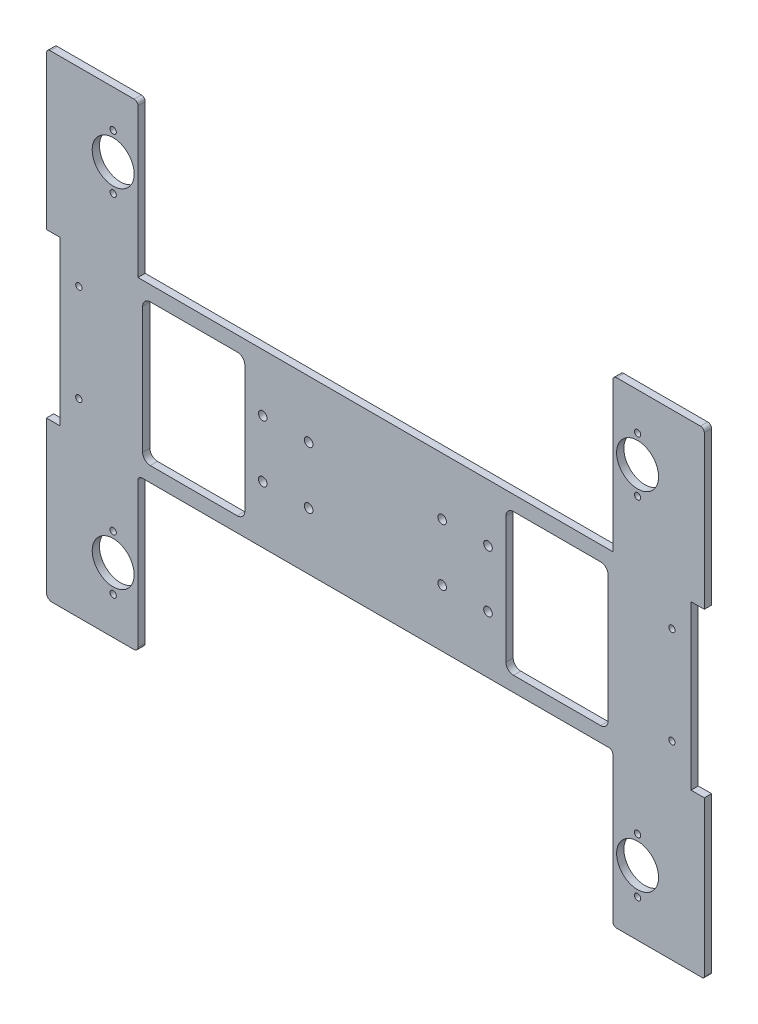
SolidWorks part; units mm, degrees
ref_plane "Front Plane" through (0, 0, 0) normal (0, 0, 1) x (1, 0, 0)
ref_plane "Top Plane" through (0, 0, 0) normal (0, 1, 0) x (1, 0, 0)
ref_plane "Right Plane" through (0, 0, 0) normal (1, 0, 0) x (0, 0, -1)
ref_plane "Plane1" through (0, 150, 0) normal (0, 1, 0) x (1, 0, 0)
ref_plane "Plane2" through (0, -150, 0) normal (0, 1, 0) x (1, 0, 0)
ref_plane "Plane3" through (150, 0, 0) normal (1, 0, 0) x (0, 0, -1)
ref_plane "Plane4" through (-150, 0, 0) normal (1, 0, 0) x (0, 0, -1)
sketch "Sketch2" plane through (0, 0, 0) normal (0, 0, 1) x (1, 0, 0)
  line L0 (0, -10.2) -> (0, 50.0764) construction
  line L5 (-59.06, 39.945) -> (-59.06, 10.055) construction
  line L23 (-170.5, 150) -> (-126.5, 150)
  line L24 (139.6652, 116) -> (168.3348, 116) construction
  line L30 (-172.5, 148) -> (-172.5, 67.8042)
  line L31 (-169.5, -100) -> (-126.5, -100)
  line L39 (172.5, 148) -> (172.5, 67.8042)
  line L40 (-152.1866, -81.0661) -> (-123.5266, -81.0661) construction
  line L42 (-124.5, 148) -> (-124.5, 70)
  line L43 (-124.5, 70) -> (124.5, 70)
  line L44 (124.5, 148) -> (124.5, 70)
  line L45 (126.5, 150) -> (170.5, 150)
  line L47 (-72.4574, 62.1714) -> (-118.0552, 62.1714)
  line L48 (72.4574, 62.1714) -> (118.0552, 62.1714)
  line L49 (68.4574, 58.1714) -> (68.4574, -8.1714)
  line L50 (72.4574, -12.1714) -> (118.0552, -12.1714)
  line L51 (122.0552, 58.1714) -> (122.0552, -8.1714)
  line L52 (68.4574, 62.1714) -> (122.0552, -12.1714) construction
  line L53 (68.4574, -12.1714) -> (122.0552, 62.1714) construction
  line L54 (-68.4574, 58.1714) -> (-68.4574, -8.1714)
  line L55 (-72.4574, -12.1714) -> (-118.0552, -12.1714)
  line L56 (-122.0552, 58.1714) -> (-122.0552, -8.1714)
  line L57 (177.1787, -66.0847) -> (177.1787, 11.9153) construction
  line L61 (165.5, 67.8042) -> (165.5, -17.8042)
  line L62 (165.5, -17.8042) -> (172.5, -17.8042)
  line L63 (172.5, 67.8042) -> (165.5, 67.8042)
  line L65 (172.5, -17.8042) -> (172.5, -99)
  line L66 (177.1787, 0) -> (1253.7576, 0) construction
  line L67 (-165.5, 67.8042) -> (-165.5, -17.8042)
  line L69 (-172.5, -17.8042) -> (-172.5, -97)
  line L70 (-155.5, 50.5) -> (-155.5, -0.5) construction
  line L71 (-172.5, 67.8042) -> (-165.5, 67.8042)
  line L72 (-172.5, -17.8042) -> (-165.5, -17.8042)
  line L74 (162.5, 25) -> (139.6652, 25) construction
  line L75 (-124.5, -98) -> (-124.5, -22)
  line L76 (-122.5, -20) -> (122.5, -20)
  line L77 (124.5, -22) -> (124.5, -98)
  line L78 (126.5, -100) -> (171.5, -100)
  circle A1 centre (-137.5, 130.3348) radius 1.65
  circle A2 centre (-137.5, 101.6652) radius 1.65
  circle A3 centre (137.5, 130.3348) radius 1.65
  circle A4 centre (137.5, 101.6652) radius 1.65
  circle A9 centre (137.5, 116) radius 11
  circle A10 centre (-137.5, 116) radius 11
  circle A17 centre (155.5, -0.5) radius 1.65
  circle A18 centre (155.5, 50.5) radius 1.65
  circle A19 centre (-155.5, -0.5) radius 1.65
  circle A20 centre (-155.5, 50.5) radius 1.65
  circle A27 centre (-35, 10.055) radius 2.25
  circle A32 centre (-35, 39.945) radius 2.25
  circle A33 centre (-59.06, 39.945) radius 2.25
  circle A34 centre (-59.06, 10.055) radius 2.25
  circle A35 centre (59.06, 10.055) radius 2.25
  circle A36 centre (35, 10.055) radius 2.25
  circle A37 centre (35, 39.945) radius 2.25
  circle A38 centre (59.06, 39.945) radius 2.25
  arc A42 (-170.5, 150) -> (-172.5, 148) centre (-170.5, 148) ccw
  arc A43 (170.5, 150) -> (172.5, 148) centre (170.5, 148) cw
  arc A45 (-172.5, -97) -> (-169.5, -100) centre (-169.5, -97) ccw
  arc A46 (124.5, 148) -> (126.5, 150) centre (126.5, 148) cw
  arc A47 (-124.5, 148) -> (-126.5, 150) centre (-126.5, 148) ccw
  arc A48 (68.4574, -8.1714) -> (72.4574, -12.1714) centre (72.4574, -8.1714) ccw
  arc A49 (118.0552, -12.1714) -> (122.0552, -8.1714) centre (118.0552, -8.1714) ccw
  arc A50 (118.0552, 62.1714) -> (122.0552, 58.1714) centre (118.0552, 58.1714) cw
  arc A51 (72.4574, 62.1714) -> (68.4574, 58.1714) centre (72.4574, 58.1714) ccw
  arc A52 (-118.0552, 62.1714) -> (-122.0552, 58.1714) centre (-118.0552, 58.1714) ccw
  arc A53 (-72.4574, 62.1714) -> (-68.4574, 58.1714) centre (-72.4574, 58.1714) cw
  arc A54 (-68.4574, -8.1714) -> (-72.4574, -12.1714) centre (-72.4574, -8.1714) cw
  arc A55 (-118.0552, -12.1714) -> (-122.0552, -8.1714) centre (-118.0552, -8.1714) cw
  arc A64 (172.5, -99) -> (171.5, -100) centre (171.5, -99) cw
  circle A68 centre (137.5, -80.3348) radius 1.65
  circle A69 centre (137.5, -51.6652) radius 1.65
  circle A70 centre (137.5, -66) radius 11
  circle A71 centre (-137.5, -66) radius 11
  circle A72 centre (-137.5, -51.6652) radius 1.65
  circle A73 centre (-137.5, -80.3348) radius 1.65
  arc A74 (124.5, -98) -> (126.5, -100) centre (126.5, -98) ccw
  arc A75 (122.5, -20) -> (124.5, -22) centre (122.5, -22) cw
  arc A76 (-124.5, -22) -> (-122.5, -20) centre (-122.5, -22) cw
  arc A77 (-124.5, -98) -> (-126.5, -100) centre (-126.5, -98) cw
  point P0 (0, 0)
  point P2 (0, 0)
  point P4 (0, 150)
  point P11 (-155.5, 25)
  point P12 (95.2563, 25)
  point P23 (-59.06, 25)
  point P24 (124.5, -100)
  point P39 (-165.5, 25)
  point P45 (124.5, 150)
  point P82 (177.1787, -27.0847)
  point P111 (-122.0552, 25)
  point P132 (-68.4574, 25)
  dimension "D3" = 51
  dimension "D7" = 13
  dimension "D8" = 3.3
  dimension "D9" = 35
  dimension "D10" = 22
  dimension "D11" = 74.3428
  dimension "D12" = 13
  dimension "D13" = 53.5977
  dimension "D16" = 68.4574
  dimension "D17" = 13
  dimension "D18" = 2
  dimension "D19" = 3.3
  dimension "D6" = 14.3348
  dimension "D20" = 14.3348
  dimension "D21" = 2
  dimension "D23" = 4.5
  dimension "D25" = 4.5
  dimension "D26" = 4.5
  dimension "D27" = 29.89
  dimension "D29" = 24.06
  dimension "D31" = 4
  dimension "D32" = 7
  dimension "D33" = 1
  dimension "D35" = 85.6084
  dimension "D36" = 80
  dimension "D37" = 80
  dimension "D4" = 3.3
  dimension "D5" = 10
  dimension "D22" = 29.89
  dimension "D28" = 24.06
  dimension "D30" = 35
  dimension "D15" = 2
  dimension "D14" = 45
extrude "Boss-Extrude1" add sketch "Sketch2" along normal blind 3.8
